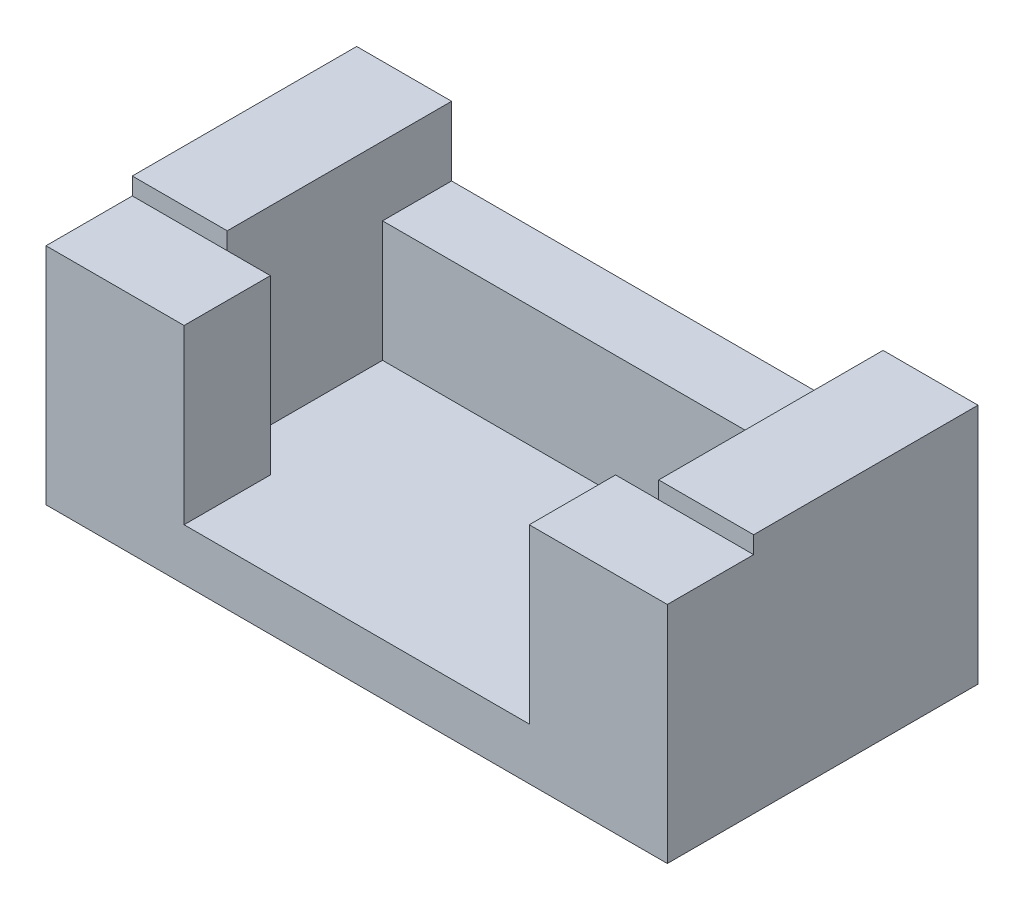
SolidWorks part; units mm, degrees
ref_plane "前视基准面" through (0, 0, 0) normal (0, 0, 1) x (1, 0, 0)
ref_plane "上视基准面" through (0, 0, 0) normal (0, 1, 0) x (1, 0, 0)
ref_plane "右视基准面" through (0, 0, 0) normal (1, 0, 0) x (0, 0, -1)
sketch "草图1" plane through (0, 0, 0) normal (0, 1, 0) x (1, 0, 0)
  line L1 (-18, 9) -> (18, 9)
  line L2 (-18, 9) -> (-18, -9)
  line L3 (-18, -9) -> (18, -9)
  line L4 (18, 9) -> (18, -9)
  line L5 (-18, 9) -> (18, -9) construction
  line L6 (-18, -9) -> (18, 9) construction
  point P0 (0, 0)
  dimension "D1" = 36
  dimension "D2" = 18
extrude "凸台-拉伸1" add sketch "草图1" along normal blind 3
sketch "草图2" plane through (0, 3, 0) normal (0, 1, 0) x (1, 0, 0)
  line L0 (0, 0) -> (0, -13.6636) construction
  line L1 (-18, -9) -> (-10, -9)
  line L2 (-18, -9) -> (-18, -4)
  line L3 (-18, -4) -> (-10, -4)
  line L4 (-10, -9) -> (-10, -4)
  line L5 (10, -9) -> (10, -4)
  line L6 (18, -4) -> (10, -4)
  line L7 (18, -9) -> (18, -4)
  line L8 (18, -9) -> (10, -9)
  dimension "D1" = 5
  dimension "D2" = 20
extrude "凸台-拉伸2" add sketch "草图2" along normal blind 10
sketch "草图3" plane through (0, 3, 0) normal (0, 1, 0) x (1, 0, 0)
  line L0 (-18, 9) -> (-18, -4)
  line L1 (-18, 9) -> (-18, -4) construction
  line L2 (-18, -4) -> (-12.5, -4)
  line L3 (-12.5, -4) -> (-12.5, 5)
  line L4 (-12.5, 5) -> (12.5, 5)
  line L5 (12.5, 5) -> (12.5, -4)
  line L6 (12.5, -4) -> (18, -4)
  line L7 (18, -4) -> (18, 9) construction
  line L8 (18, -4) -> (18, 9)
  line L9 (18, 9) -> (-18, 9)
  line L10 (0, 0) -> (0, 12.8428) construction
  line L11 (-10, -4) -> (-18, -4) construction
  line L12 (-10, -4) -> (-18, -4) construction
  dimension "D1" = 0
  dimension "D2" = 9
  dimension "D3" = 25
extrude "凸台-拉伸3" add sketch "草图3" along normal blind 11
sketch "草图4" plane through (0, 14, 0) normal (0, 1, 0) x (1, 0, 0)
  line L0 (18, 9) -> (-18, 9) construction
  line L1 (-12.5, 5) -> (12.5, 5)
  line L2 (-12.5, 5) -> (-12.5, 9)
  line L3 (-12.5, 9) -> (12.5, 9)
  line L4 (12.5, 5) -> (12.5, 9)
extrude "切除-拉伸1" cut sketch "草图4" against normal blind 4
